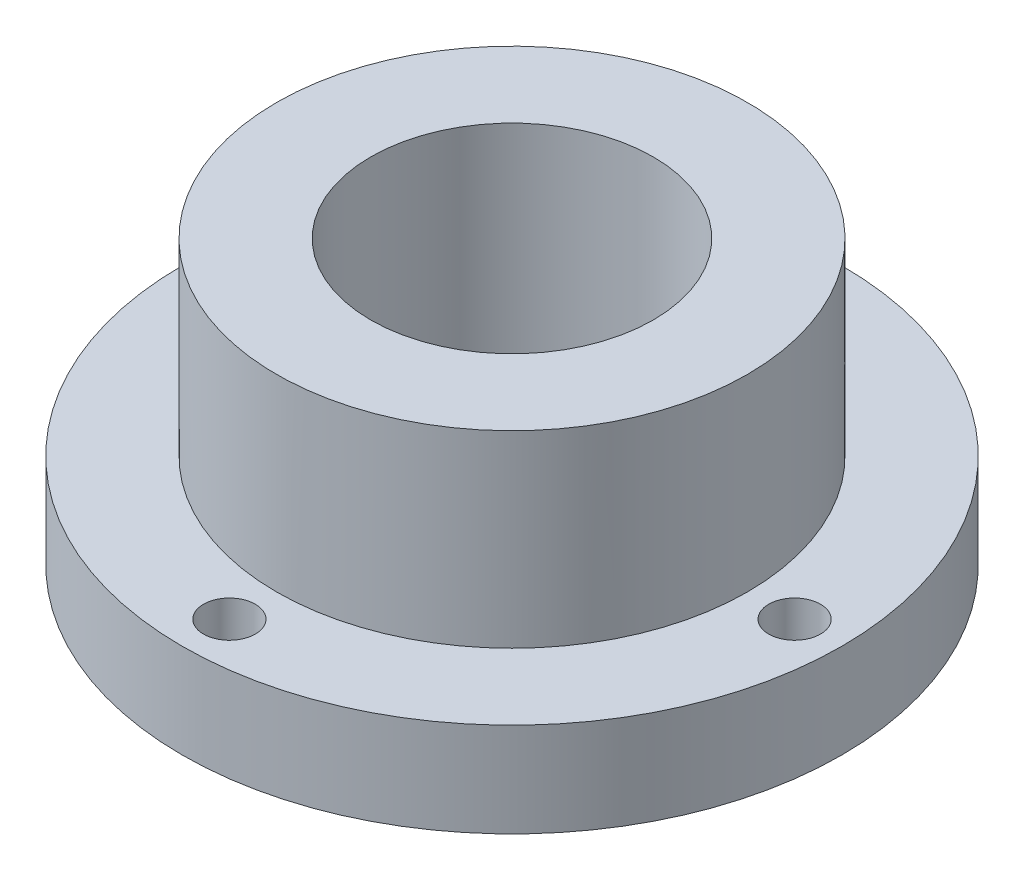
SolidWorks part; units mm, degrees
ref_plane "前视基准面" through (0, 0, 0) normal (0, 0, 1) x (1, 0, 0)
ref_plane "上视基准面" through (0, 0, 0) normal (0, 1, 0) x (1, 0, 0)
ref_plane "右视基准面" through (0, 0, 0) normal (1, 0, 0) x (0, 0, -1)
sketch "草图1" plane through (0, 0, 0) normal (0, 1, 0) x (1, 0, 0)
  circle A0 centre (0, 0) radius 35
  dimension "D1" = 70
extrude "凸台-拉伸1" add sketch "草图1" along normal blind 10
sketch "草图4" plane through (0, 0, 0) normal (0, -1, 0) x (1, 0, 0)
  circle A0 centre (0, 0) radius 15
  dimension "D1" = 30
extrude "拉伸-薄壁1" add sketch "草图4" against normal blind 30 thin
sketch "草图5" plane through (0, 10, 0) normal (0, 1, 0) x (1, 0, 0)
  circle A0 centre (0, 0) radius 30 construction
  point P3 (30, 0)
  point P7 (0, -30)
  point P8 (-30, 0)
  point P9 (0, 30)
  dimension "D1" = 60
  dimension "D2" = 4
hole_wizard "孔1" positions "草图5" profile "草图6" legacy end condition up to next
sketch "草图6" plane through (0, 10, -30) normal (1, 0, 0) x (0, 0, 1)
  line L0 (0, 0) -> (0, 10)
  line L1 (0, 10) -> (2.75, 10)
  line L2 (2.75, 10) -> (2.75, 0)
  line L3 (2.75, 0) -> (0, 0)
  line L4 (0, 110) -> (0, -10) construction
  dimension "直径" = 5.5
  dimension "深度" = 10
sketch "草图7" plane through (0, 10, 0) normal (0, 1, 0) x (1, 0, 0)
  circle A0 centre (0, 0) radius 15
  dimension "D1" = 30
extrude "切除-拉伸1" cut sketch "草图7" against normal through all
